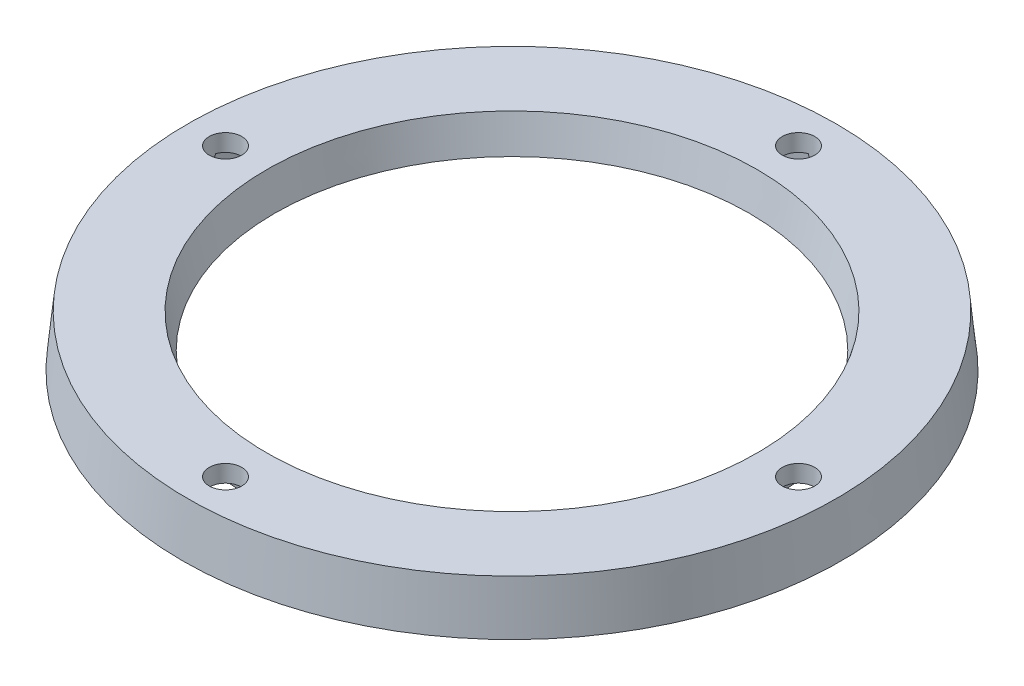
SolidWorks part; units mm, degrees
ref_plane "Front Plane" through (0, 0, 0) normal (0, 0, 1) x (1, 0, 0)
ref_plane "Top Plane" through (0, 0, 0) normal (0, 1, 0) x (1, 0, 0)
ref_plane "Right Plane" through (0, 0, 0) normal (1, 0, 0) x (0, 0, -1)
sketch "Sketch1" plane through (0, 0, 0) normal (1, 0, 0) x (0, 0, -1)
  line L0 (-27.085, 0) -> (-26.665, 4.22)
  line L1 (-26.665, 4.22) -> (-20.165, 4.22)
  line L2 (-20.165, 4.22) -> (-19.515, 1.43)
  line L3 (-19.515, 1.43) -> (-21.195, 1.43)
  line L4 (-21.195, 1.43) -> (-21.5165, 2.81)
  line L5 (-21.5165, 2.81) -> (-24.8053, 2.81)
  line L6 (-24.8053, 2.81) -> (-25.085, 0)
  line L7 (-25.085, 0) -> (-27.085, 0)
  line L8 (0, 0) -> (0, 8.6241) construction
  point P11 (0, 0)
  point P12 (-20.9254, 1.43)
  dimension "D1" = 54.17
  dimension "D2" = 4.22
  dimension "D3" = 53.33
  dimension "D4" = 2
  dimension "D5" = 2.81
  dimension "D6" = 1.43
  dimension "D7" = 1.68
  dimension "D8" = 6.5
  dimension "D9" = 7.57
revolve "Revolve1" add sketch "Sketch1" angle 360 about L8
sketch "Sketch2" plane through (0, 4.22, 0) normal (0, 1, 0) x (1, 0, 0)
  line L0 (-27.085, 0) -> (27.085, 0) construction
  line L1 (0, 27.085) -> (0, -27.085) construction
  line L2 (-23.5467, 0) -> (0, 23.5467) construction
  circle A0 centre (0, 0) radius 27.085 construction
  circle A1 centre (-23.5467, 0) radius 1.335
  circle A2 centre (0, 23.5467) radius 1.335
  circle A3 centre (23.5467, 0) radius 1.335
  circle A4 centre (0, -23.5467) radius 1.335
  circle A5 centre (0, 0) radius 23.5467 construction
  dimension "D1" = 2.67
  dimension "D2" = 33.3
extrude "Cut-Extrude1" cut sketch "Sketch2" against normal through all both and the other way through all
